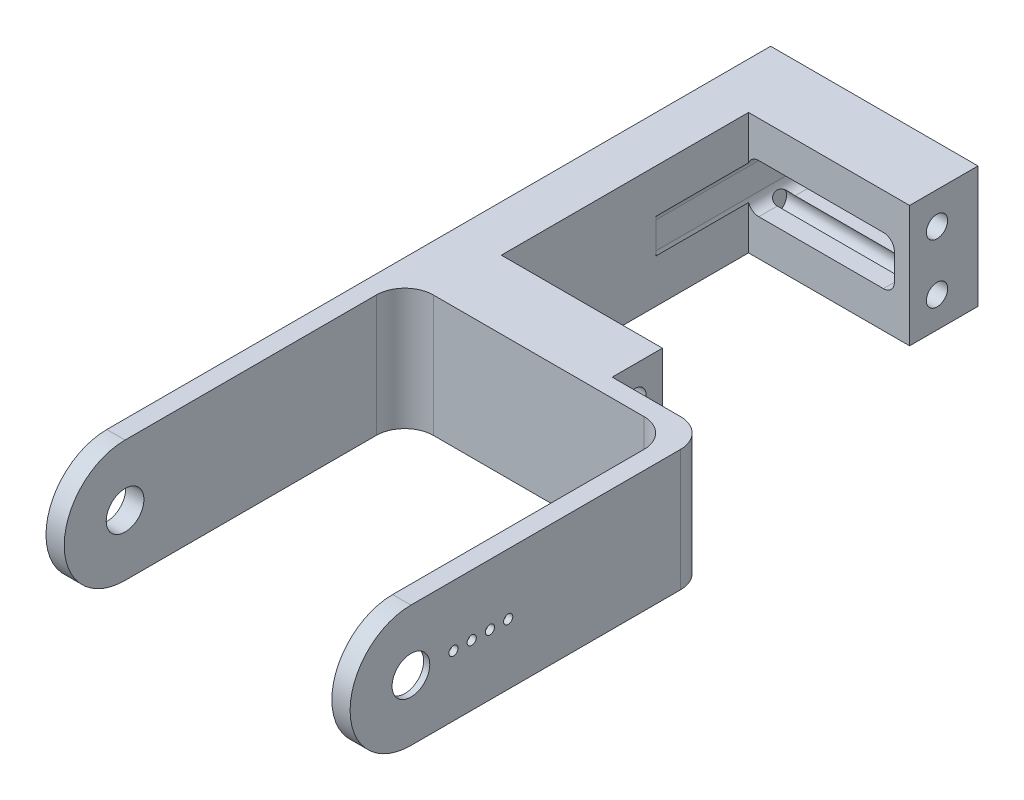
SolidWorks part; units mm, degrees
ref_plane "Vorne" through (0, 0, 0) normal (0, 0, 1) x (1, 0, 0)
ref_plane "Oben" through (0, 0, 0) normal (0, 1, 0) x (1, 0, 0)
ref_plane "Rechts" through (0, 0, 0) normal (1, 0, 0) x (0, 0, -1)
sketch "Skizze1" plane through (0, 0, 0) normal (0, 1, 0) x (1, 0, 0)
  line L1 (0, 0) -> (50, 0)
  line L2 (0, 0) -> (0, 59)
  line L3 (0, 59) -> (45.3, 59)
  line L4 (50, 0) -> (50, 54.3)
  line L5 (47, 0) -> (3, 0)
  line L6 (47, 0) -> (47, 51.3)
  line L7 (42.3, 56) -> (7.7, 56)
  line L8 (3, 0) -> (3, 51.3)
  arc A0 (47, 51.3) -> (42.3, 56) centre (42.3, 51.3) ccw
  arc A1 (7.7, 56) -> (3, 51.3) centre (7.7, 51.3) ccw
  arc A2 (45.3, 59) -> (50, 54.3) centre (45.3, 54.3) cw
  dimension "D6" = 4.7
  dimension "D7" = 4.7
  dimension "D1" = 59
  dimension "D2" = 50
  dimension "D3" = 3
  dimension "D4" = 3
  dimension "D5" = 3
extrude "Aufsatz-Linear austragen1" add sketch "Skizze1" along normal blind 20 contours L1 L8 L7 L6 L4 L3 L2
sketch "Skizze2" plane through (50, 0, 0) normal (1, 0, 0) x (0, 0, -1)
  line L0 (0, 20) -> (0, 0) construction
  line L1 (10, 20) -> (0, 20)
  line L2 (0, 20) -> (0, 0)
  line L3 (0, 0) -> (10, 0)
  arc A0 (10, 20) -> (10, 0) centre (10, 10) ccw
  line M1 (0, 0) -> (54.3, 0)
  line M3 (54.3, 20) -> (0, 20)
  line M4 (0, 20) -> (0, 0)
  dimension "D1" = 10
extrude "Schnitt-Linear austragen1" cut sketch "Skizze2" against normal blind 53.24 contours A0 M3 M4 | A0 L2 M1
sketch "Skizze3" plane through (50, 0, 0) normal (1, 0, 0) x (0, 0, -1)
  circle A0 centre (10, 10) radius 3.1
  dimension "D1" = 6.2
extrude "Schnitt-Linear austragen2" cut sketch "Skizze3" against normal blind 53.24
sketch "Skizze4" plane through (47, 0, 0) normal (-1, 0, 0) x (0, 0, 1)
  line L0 (-27.5, 12.5) -> (-14.8073, 14.375)
  line L1 (-27.5, 7.5) -> (-14.8073, 5.625)
  arc A0 (-14.8073, 5.625) -> (-14.8073, 14.375) centre (-10, 10) ccw
  arc A1 (-27.5, 12.5) -> (-27.5, 7.5) centre (-27.5, 10) ccw
  arc A2 (-10, 0) -> (-10, 20) centre (-10, 10) ccw construction
  dimension "D1" = 0
extrude "Schnitt-Linear austragen3" cut sketch "Skizze4" against normal blind 2
sketch "Skizze5" plane through (49, 0, 0) normal (-1, 0, 0) x (0, 0, 1)
  circle A0 centre (-25.9955, 10) radius 0.75
  circle A1 centre (-22.9955, 10) radius 0.75
  circle A2 centre (-19.9955, 10) radius 0.75
  circle A3 centre (-16.9955, 10) radius 0.75
  circle A4 centre (-10, 10) radius 3.1 construction
  dimension "D1" = 3
  dimension "D2" = 3
  dimension "D3" = 3
  dimension "D4" = 6.9955
  dimension "D5" = 0
extrude "Schnitt-Linear austragen4" cut sketch "Skizze5" against normal blind 2
sketch "Skizze6" plane through (0, 0, 0) normal (0, -1, 0) x (1, 0, 0)
  line L2 (34.094, -59.2569) -> (34.094, -67.2569)
  line L3 (34.094, -67.2569) -> (0, -67.2569)
  line L4 (0, -59.2569) -> (0, -67.2569)
  line L6 (0, -59.2569) -> (0, -57.8944)
  line L7 (0, -57.8944) -> (34.094, -57.8944)
  line L8 (34.094, -59.2569) -> (34.094, -57.8944)
extrude "Aufsatz-Linear austragen2" add sketch "Skizze6" against normal blind 20
sketch "Skizze7" plane through (0, 0, 0) normal (0, -1, 0) x (1, 0, 0)
  line L1 (0, -67.2569) -> (7.6117, -67.2569)
  line L2 (0, -67.2569) -> (0, -119.1478)
  line L3 (0, -119.1478) -> (7.6117, -119.1478)
  line L4 (7.6117, -67.2569) -> (7.6117, -119.1478)
extrude "Aufsatz-Linear austragen3" add sketch "Skizze7" against normal blind 20
sketch "Skizze8" plane through (7.6117, 0, 0) normal (1, 0, 0) x (0, 0, -1)
  line L1 (119.1478, 20) -> (107.8992, 20)
  line L2 (119.1478, 20) -> (119.1478, 0)
  line L3 (119.1478, 0) -> (107.8992, 0)
  line L4 (107.8992, 20) -> (107.8992, 0)
  line L5 (119.1478, 0) -> (67.2569, 0) construction
  dimension "D1" = 0
extrude "Aufsatz-Linear austragen4" add sketch "Skizze8" along normal blind 26.48
sketch "Skizze9" plane through (0, 0, -119.1478) normal (0, 0, -1) x (-1, 0, 0)
  line L0 (0, 20) -> (-34.0917, 20) construction
  line L1 (-9.3, 14) -> (-29.794, 14)
  line L2 (-7.5, 12.2) -> (-7.5, 7.8)
  line L3 (-9.3, 6) -> (-29.794, 6)
  line L4 (-31.594, 12.2) -> (-31.594, 7.8)
  line L5 (0, 0) -> (-34.0917, 0) construction
  line L6 (-34.094, 18.9) -> (-34.094, 0.9) construction
  line L7 (0, 20) -> (0, 0) construction
  arc A0 (-9.3, 14) -> (-7.5, 12.2) centre (-9.3, 12.2) cw
  arc A1 (-7.5, 7.8) -> (-9.3, 6) centre (-9.3, 7.8) cw
  arc A2 (-29.794, 6) -> (-31.594, 7.8) centre (-29.794, 7.8) cw
  arc A3 (-29.794, 14) -> (-31.594, 12.2) centre (-29.794, 12.2) ccw
  dimension "D5" = 1.8
  dimension "D1" = 6
  dimension "D2" = 6
  dimension "D3" = 2.5
  dimension "D4" = 7.5
extrude "Schnitt-Linear austragen5" cut sketch "Skizze9" against normal blind 26.48
sketch "Skizze10" plane through (34.0917, 0, 0) normal (1, 0, 0) x (0, 0, -1)
  circle A0 centre (62.8069, 14.75) radius 1.75
  circle A1 centre (62.8069, 5.05) radius 1.75
  circle A2 centre (112.4069, 5.05) radius 1.75
  circle A3 centre (112.4069, 14.75) radius 1.75
  dimension "D1" = 3.5
  dimension "D2" = 3.5
  dimension "D3" = 3.5
  dimension "D4" = 3.5
extrude "Schnitt-Linear austragen6" cut sketch "Skizze10" against normal blind 26.48 and the other way blind 6
sketch "Skizze11" plane through (0, 0, 0) normal (-1, 0, 0) x (0, 0, 1)
  circle A0 centre (-99.4569, 9.9) radius 3
  dimension "D1" = 6
extrude "Aufsatz-Linear austragen5" add sketch "Skizze11" along normal blind 6
